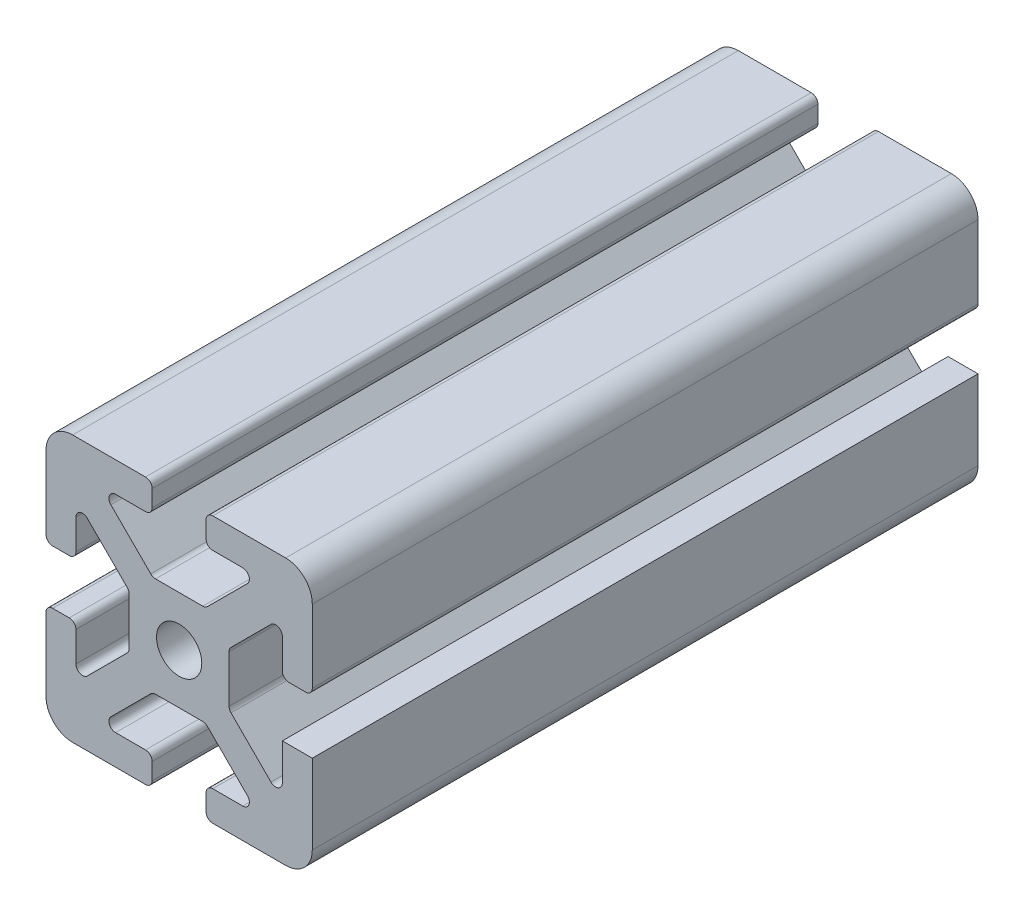
SolidWorks part; units mm, degrees
other "Markierung1"
sketch "Skizze2" plane through (-20, 20, 100) normal (-0.3911, 0.1356, 0.9103) x (0.918, -0.0129, 0.3963)
ref_plane "Front" through (0, 0, 0) normal (0, 0, 1) x (1, 0, 0)
ref_plane "Top" through (0, 0, 0) normal (0, 1, 0) x (1, 0, 0)
ref_plane "Right" through (0, 0, 0) normal (1, 0, 0) x (0, 0, -1)
sketch "Skizze1" plane through (0, 0, 0) normal (0, 0, 1) x (1, 0, 0)
  line L0 (0, 20) -> (0, 0) construction
  line L1 (-20, -20) -> (-4.05, -20)
  line L2 (-20, -20) -> (-20, -4.05)
  line L3 (-20, 20) -> (-4.05, 20)
  line L4 (20, -20) -> (20, -4.05)
  line L5 (-20, -20) -> (20, 20) construction
  line L6 (-20, 20) -> (20, -20) construction
  line L7 (4.05, 20) -> (4.05, 15.5)
  line L8 (4.05, 15.5) -> (11.9645, 15.5)
  line L9 (11.9645, 15.5) -> (3.9645, 7.5)
  line L10 (3.9645, 7.5) -> (-3.9645, 7.5)
  line L11 (0, 0) -> (20, 0) construction
  line L12 (-11.9645, 15.5) -> (-3.9645, 7.5)
  line L13 (-4.05, 15.5) -> (-11.9645, 15.5)
  line L14 (-4.05, 20) -> (-4.05, 15.5)
  line L15 (4.05, 20) -> (20, 20)
  line L16 (20, 4.05) -> (15.5, 4.05)
  line L17 (15.5, 4.05) -> (15.5, 11.9645)
  line L18 (15.5, 11.9645) -> (7.5, 3.9645)
  line L19 (15.5, -11.9645) -> (7.5, -3.9645)
  line L20 (7.5, 3.9645) -> (7.5, -3.9645)
  line L21 (20, -4.05) -> (15.5, -4.05)
  line L22 (15.5, -4.05) -> (15.5, -11.9645)
  line L23 (4.05, -20) -> (4.05, -15.5)
  line L24 (4.05, -15.5) -> (11.9645, -15.5)
  line L25 (11.9645, -15.5) -> (3.9645, -7.5)
  line L26 (-3.9645, -7.5) -> (3.9645, -7.5)
  line L27 (-11.9645, -15.5) -> (-3.9645, -7.5)
  line L28 (-4.05, -15.5) -> (-11.9645, -15.5)
  line L29 (-4.05, -20) -> (-4.05, -15.5)
  line L30 (-15.5, -4.05) -> (-15.5, -11.9645)
  line L31 (-15.5, -11.9645) -> (-7.5, -3.9645)
  line L32 (-15.5, 11.9645) -> (-7.5, 3.9645)
  line L33 (-7.5, -3.9645) -> (-7.5, 3.9645)
  line L34 (-20, 4.05) -> (-15.5, 4.05)
  line L35 (-15.5, 4.05) -> (-15.5, 11.9645)
  line L36 (-20, -4.05) -> (-15.5, -4.05)
  line L37 (-20, 4.05) -> (-20, 20)
  line L38 (4.05, -20) -> (20, -20)
  line L39 (20, 4.05) -> (20, 20)
  circle A0 centre (0, 0) radius 3.4
  point P0 (0, 0)
  point P14 (0, 7.5)
  dimension "D6" = 6.8
  dimension "D1" = 40
  dimension "D2" = 8.1
  dimension "D3" = 5
  dimension "D4" = 4.5
  dimension "D5" = 15
extrude "Aufsatz-Linear austragen1" add sketch "Skizze1" along normal blind 100
fillet "Verrundung1" radius 4 4 edges at (20, -20, 50) (-20, -20, 50) (-20, 20, 50) (20, 20, 50)
fillet "Verrundung2" radius 1 30 edges at (4.05, -20, 50) (4.05, -15.5, 50) (-4.05, -20, 50) (-4.05, -15.5, 50) (-20, -4.05, 50) (-15.5, -4.05, 50) (-20, 4.05, 50) (-15.5, 4.05, 50) (3.9645, -7.5, 50) (-3.9645, -7.5, 50) (-11.9645, -15.5, 50) (11.9645, -15.5, 50) (20, 4.05, 50) (15.5, 4.05, 50) (15.5, 11.9645, 50) (15.5, -11.9645, 50) (7.5, -3.9645, 50) (7.5, 3.9645, 50) (-4.05, 15.5, 50) (-4.05, 20, 50) (4.05, 20, 50) (4.05, 15.5, 50) (11.9645, 15.5, 50) (3.9645, 7.5, 50) (-3.9645, 7.5, 50) (-11.9645, 15.5, 50) (-7.5, -3.9645, 50) (-7.5, 3.9645, 50) (-15.5, -11.9645, 50) (-15.5, 11.9645, 50)
